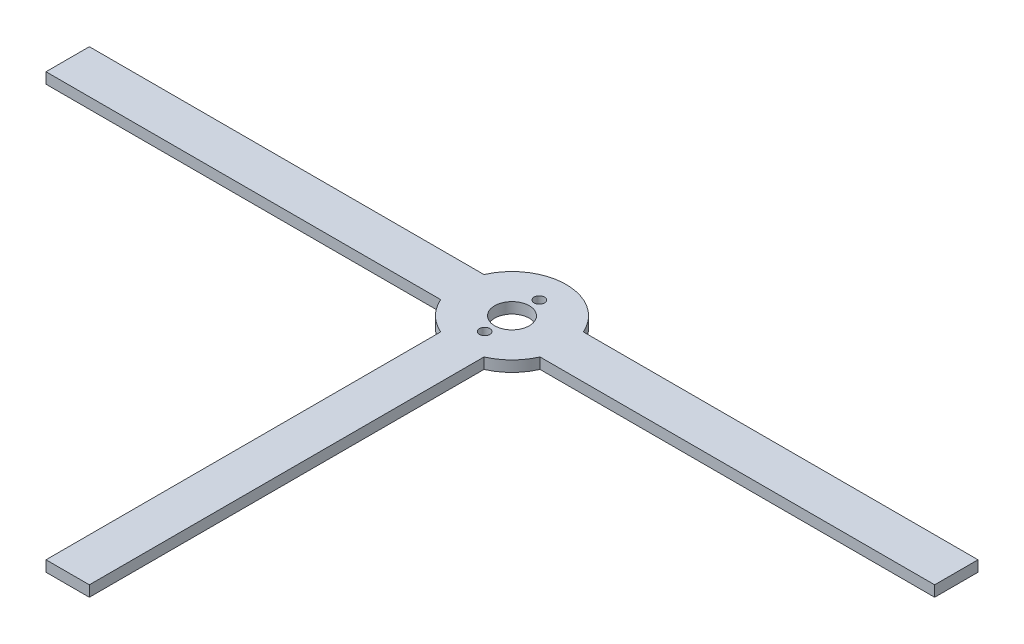
SolidWorks part; units mm, degrees
ref_plane "Front Plane" through (0, 0, 0) normal (0, 0, 1) x (1, 0, 0)
ref_plane "Top Plane" through (0, 0, 0) normal (0, 1, 0) x (1, 0, 0)
ref_plane "Right Plane" through (0, 0, 0) normal (1, 0, 0) x (0, 0, -1)
sketch "Sketch1" plane through (0, 0, 0) normal (0, 1, 0) x (1, 0, 0)
  line L0 (-14.5497, 6.35) -> (-130.175, 6.35)
  line L1 (130.175, -6.35) -> (14.5497, -6.35)
  line L2 (130.175, -6.35) -> (130.175, 6.35)
  line L3 (130.175, 6.35) -> (14.5497, 6.35)
  line L4 (-130.175, -6.35) -> (-130.175, 6.35)
  line L9 (-6.35, -130.175) -> (6.35, -130.175)
  line L12 (6.35, -14.5497) -> (6.35, -130.175)
  line L13 (-6.35, -14.5497) -> (-6.35, -130.175)
  line L14 (-14.5497, -6.35) -> (-130.175, -6.35)
  arc A2 (14.5497, 6.35) -> (-14.5497, 6.35) centre (0, 0) ccw
  arc A3 (-14.5497, -6.35) -> (-6.35, -14.5497) centre (0, 0) ccw
  arc A4 (6.35, -14.5497) -> (14.5497, -6.35) centre (0, 0) ccw
  point P0 (0, 0)
  point P11 (0, -130.175)
  dimension "D5" = 31.75
  dimension "D1" = 260.35
  dimension "D2" = 12.7
  dimension "D3" = 130.175
  dimension "D4" = 12.7
sketch "Screw holes" plane through (0, 0, 0) normal (0, 1, 0) x (1, 0, 0)
  circle A0 centre (0, 8) radius 1.5133
  circle A1 centre (0, -8) radius 1.5133
  circle A2 centre (0, 0) radius 5.08
  dimension "D1" = 16
  dimension "D3" = 3.0266
  dimension "D4" = 10.16
  dimension "D2" = 8
extrude "Boss-Extrude1" add sketch "Sketch1" along normal blind 3.175
extrude "Cut-Extrude1" cut sketch "Screw holes" along normal through all
